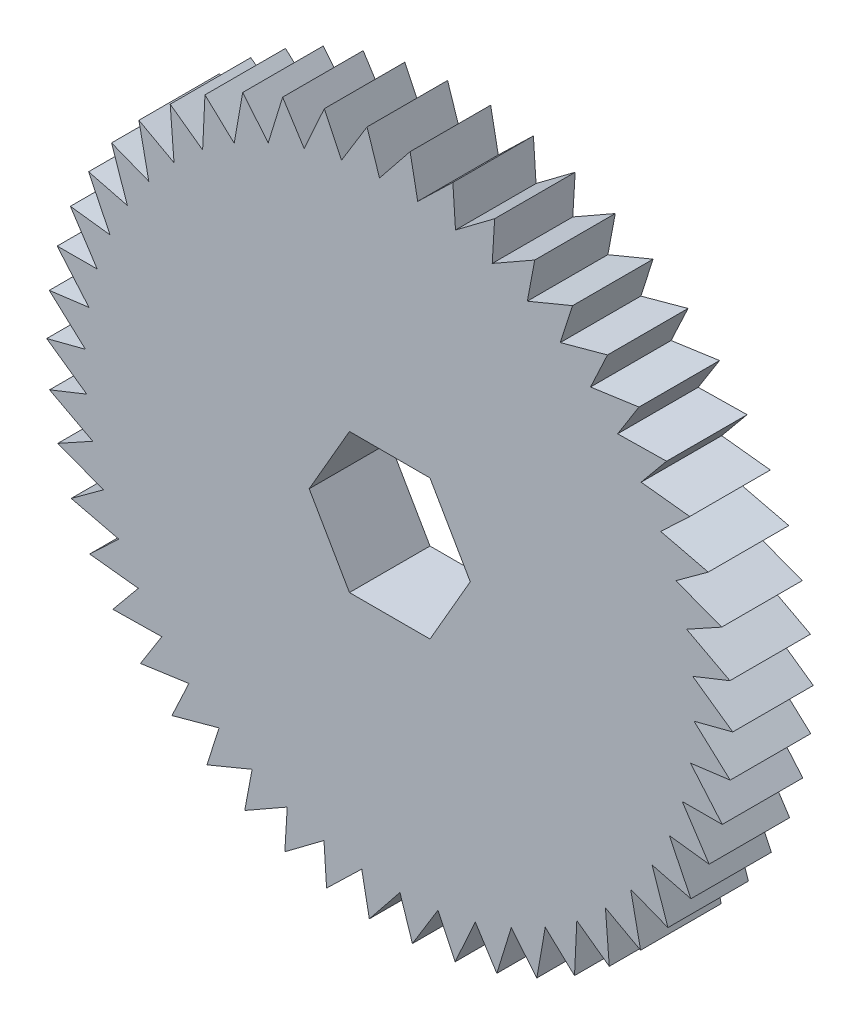
SolidWorks part; units mm, degrees
ref_plane "Piano frontale" through (0, 0, 0) normal (0, 0, 1) x (1, 0, 0)
ref_plane "Piano superiore" through (0, 0, 0) normal (0, 1, 0) x (1, 0, 0)
ref_plane "Piano destro" through (0, 0, 0) normal (1, 0, 0) x (0, 0, -1)
sketch "Schizzo1" plane through (0, 0, 0) normal (0, 0, 1) x (1, 0, 0)
  circle A0 centre (0, 0) radius 42.7013
extrude "Estrusione-Estrusione2" add sketch "Schizzo1" along normal mid plane 10
sketch "Schizzo6" plane through (0, 0, 5) normal (0, 0, 1) x (1, 0, 0)
  line L1 (10, 0) -> (5, 8.6603)
  line L2 (5, 8.6603) -> (-5, 8.6603)
  line L3 (-5, 8.6603) -> (-10, 0)
  line L4 (-10, 0) -> (-5, -8.6603)
  line L5 (-5, -8.6603) -> (5, -8.6603)
  line L6 (5, -8.6603) -> (10, 0)
  circle A0 centre (0, 0) radius 8.6603 construction
  dimension "D1" = 10
extrude "Taglio-Estrusione4" cut sketch "Schizzo6" against normal through all both and the other way through all
sketch "Schizzo7" plane through (0, 0, 5) normal (0, 0, 1) x (1, 0, 0)
  line L0 (-9.418, 44.5461) -> (-5.9933, 37.3162)
  line L1 (-5.9933, 37.3162) -> (-1.0876, 45.3162)
  line L2 (-1.0876, 45.3162) -> (-9.418, 44.5461)
  dimension "D1" = 8
  dimension "D2" = 8.3303
  dimension "D3" = 8
extrude "Taglio-Estrusione5" cut sketch "Schizzo7" against normal through all
pattern_circular "RipetizioneCircolare1" count 50 over 360 about axis through (0, 0, 0) along (0, 0, 1) of "Taglio-Estrusione5"
